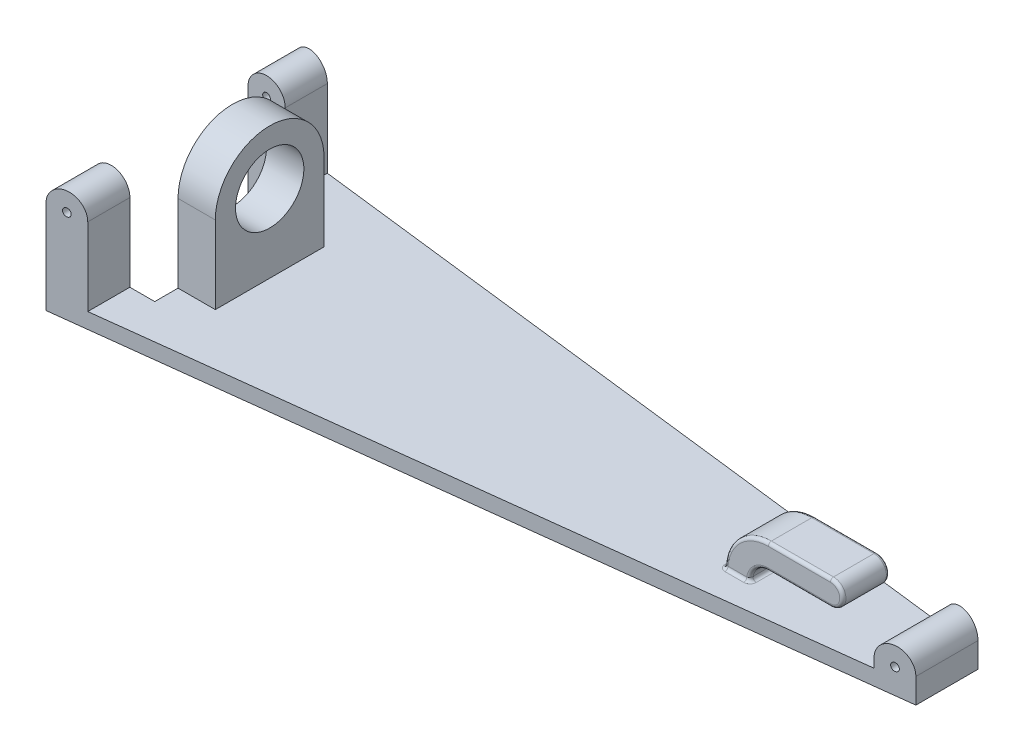
SolidWorks part; units mm, degrees
ref_plane "Front Plane" through (0, 0, 0) normal (0, 0, 1) x (1, 0, 0)
ref_plane "Top Plane" through (0, 0, 0) normal (0, 1, 0) x (1, 0, 0)
ref_plane "Right Plane" through (0, 0, 0) normal (1, 0, 0) x (0, 0, -1)
sketch "Sketch1" plane through (0, 0, 0) normal (0, 1, 0) x (1, 0, 0)
  line L0 (0, -40) -> (0, 40)
  line L13 (250, -10) -> (250, 10)
  line L14 (0, -40) -> (250, -10)
  line L19 (250, 10) -> (0, 40)
  point P3 (0, 0)
  point P6 (250, 0)
  dimension "D1" = 20
  dimension "D2" = 80
  dimension "D3" = 250
extrude "Boss-Extrude1" add sketch "Sketch1" along normal blind 5
sketch "Sketch2" plane through (0, 0, 0) normal (0, 0, 1) x (1, 0, 0)
  line L0 (0, 5) -> (250, 5) construction
  line L1 (0, 5) -> (250, 5)
  line L2 (0, 5) -> (0, 30)
  line L3 (12, 5) -> (12, 30)
  line L4 (250, 5) -> (250, 8)
  line L5 (238, 5) -> (238, 8)
  arc A0 (0, 30) -> (12, 30) centre (6, 30) cw
  circle A2 centre (244, 8) radius 1.25
  arc A3 (238, 8) -> (250, 8) centre (244, 8) cw
  circle A4 centre (6, 30) radius 1.25
  point P15 (0, 0)
  point P16 (0, 0)
  point P17 (0, 0)
  point P18 (232.7749, 10.9069)
  dimension "D1" = 25
  dimension "D2" = 6
  dimension "D4" = 3
  dimension "D3" = 2.5
extrude "Boss-Extrude2" add sketch "Sketch2" along normal up to surface and the other way up to surface
sketch "Sketch4" plane through (0, 0, 0) normal (0, 1, 0) x (1, 0, 0)
  line L1 (0, 25) -> (20, 25)
  line L2 (0, 25) -> (0, -25)
  line L3 (0, -25) -> (20, -25)
  line L4 (20, 25) -> (20, -25)
  line L5 (0, -40) -> (0, 40) construction
  point P6 (20, 0)
  point P8 (0, 0)
  dimension "D1" = 50
  dimension "D2" = 20
extrude "Cut-Extrude1" cut sketch "Sketch4" along normal through all both and the other way through all
sketch "Sketch5" plane through (20, 0, 0) normal (-1, 0, 0) x (0, 0, 1)
  line L0 (-17.5, 5) -> (-17.5, 30)
  line L1 (-25, 5) -> (25, 5) construction
  line L2 (17.5, 5) -> (17.5, 30)
  line L3 (17.5, 5) -> (-17.5, 5)
  arc A0 (-17.5, 30) -> (17.5, 30) centre (0, 30) cw
  circle A1 centre (0, 30) radius 11
  ellipse E1 centre (-39.28, 30) end of major axis (-39.28, 31.25) minor radius 0.15 construction
  ellipse E2 centre (-39.28, 30) end of major axis (-39.28, 31.25) minor radius 0.15
  point P6 (0, 5)
  point P9 (0, 0)
  point P21 (0, 0)
  point P28 (0, 0)
  line M9 (25, 5) -> (-25, 5)
  dimension "D3" = 22
  dimension "D1" = 35
extrude "Boss-Extrude3" add sketch "Sketch5" against normal blind 12 contours A1 L2 A0 L0 M9
sketch "Sketch6" plane through (0, 0, 0) normal (0, 0, 1) x (1, 0, 0)
  line L0 (12, 5) -> (238, 5) construction
  line L1 (200, 11) -> (220, 11)
  line L2 (220, 19) -> (200, 19)
  line L3 (250, 8) -> (250, 0) construction
  line L4 (194, 5) -> (186, 5)
  arc A0 (220, 19) -> (220, 11) centre (220, 15) cw
  arc A1 (200, 19) -> (186, 5) centre (200, 5) ccw
  arc A2 (194, 5) -> (200, 11) centre (200, 5) cw
  dimension "D1" = 4
  dimension "D2" = 6
  dimension "D3" = 20
  dimension "D4" = 50
extrude "Boss-Extrude4" add sketch "Sketch6" along normal mid plane 15
fillet "Fillet1" radius 1 14 edges at (194, 5, 0) (186, 5, 0) (210, 19, -7.5) (190.1005, 14.8995, -7.5) (190, 5, -7.5) (195.7574, 9.2426, -7.5) (210, 11, -7.5) (224, 15, -7.5) (210, 11, 7.5) (195.7574, 9.2426, 7.5) (190, 5, 7.5) (190.1005, 14.8995, 7.5) (210, 19, 7.5) (224, 15, 7.5)
